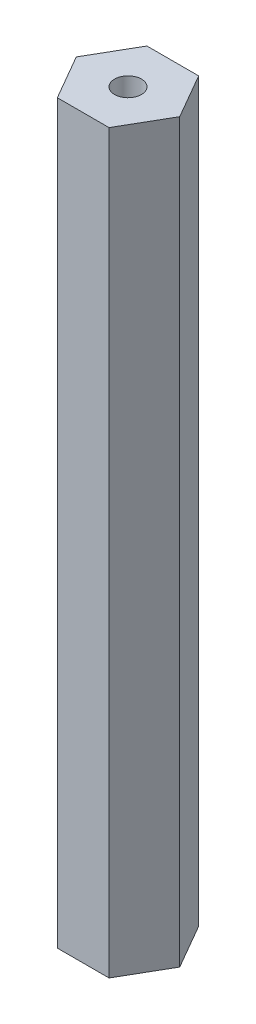
SolidWorks part; units mm, degrees
ref_plane "Спереди" through (0, 0, 0) normal (0, 0, 1) x (1, 0, 0)
ref_plane "Сверху" through (0, 0, 0) normal (0, 1, 0) x (1, 0, 0)
ref_plane "Справа" through (0, 0, 0) normal (1, 0, 0) x (0, 0, -1)
sketch "Эскиз1" plane through (0, 0, 0) normal (0, 1, 0) x (1, 0, 0)
  line L1 (2.8868, 0) -> (1.4434, 2.5)
  line L2 (1.4434, 2.5) -> (-1.4434, 2.5)
  line L3 (-1.4434, 2.5) -> (-2.8868, 0)
  line L4 (-2.8868, 0) -> (-1.4434, -2.5)
  line L5 (-1.4434, -2.5) -> (1.4434, -2.5)
  line L6 (1.4434, -2.5) -> (2.8868, 0)
  circle A0 centre (0, 0) radius 2.5 construction
  point P1 (0, 0)
  dimension "D1" = 5
extrude "Бобышка-Вытянуть1" add sketch "Эскиз1" along normal blind 41.1
sketch "Эскиз2" plane through (0, 41.1, 0) normal (0, 1, 0) x (1, 0, 0)
  circle A0 centre (0, 0) radius 0.75
  dimension "D1" = 1.5
extrude "Вырез-Вытянуть1" cut sketch "Эскиз2" against normal through all
